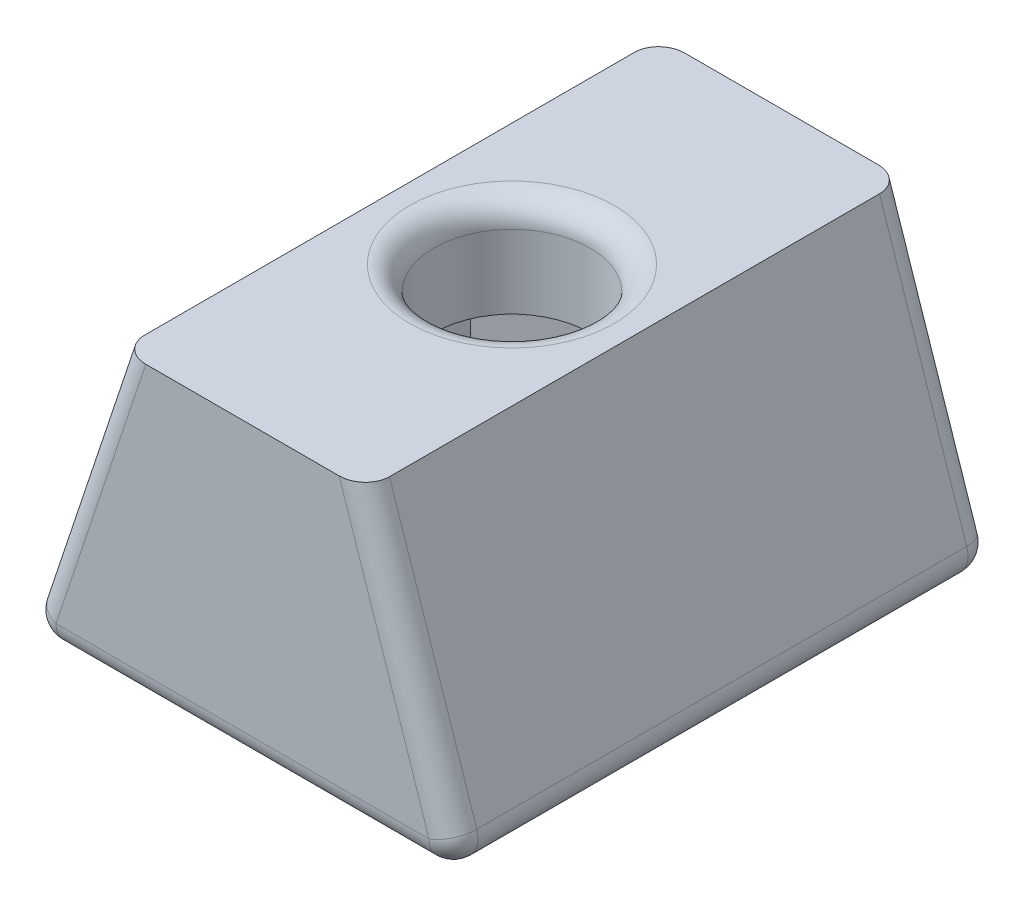
SolidWorks part; units mm, degrees
ref_plane "Front Plane" through (0, 0, 0) normal (0, 0, 1) x (1, 0, 0)
ref_plane "Top Plane" through (0, 0, 0) normal (0, 1, 0) x (1, 0, 0)
ref_plane "Right Plane" through (0, 0, 0) normal (1, 0, 0) x (0, 0, -1)
sketch "Sketch2" plane through (0, 0, 0) normal (0, 0, 1) x (1, 0, 0)
  line L0 (0, 0) -> (18, 0)
  line L1 (18, 0) -> (14.0012, 12)
  line L2 (14.0012, 12) -> (3.9988, 12)
  line L3 (3.9988, 12) -> (0, 0)
  dimension "D1" = 18
  dimension "D2" = 71.57
  dimension "D3" = 71.57
  dimension "D4" = 12
extrude "Boss-Extrude1" add sketch "Sketch2" against normal blind 22
sketch "Sketch3" plane through (0, 0, 0) normal (0, -1, 0) x (1, 0, 0)
  line L0 (0, -22) -> (0, 0) construction
  line L3 (13, -13.3094) -> (13, -8.6906)
  line L4 (13, -8.6906) -> (9, -6.3812)
  line L5 (9, -6.3812) -> (5, -8.6906)
  line L6 (5, -8.6906) -> (5, -13.3094)
  line L7 (5, -13.3094) -> (9, -15.6188)
  line L8 (9, -15.6188) -> (13, -13.3094)
  line L9 (0, 0) -> (18, 0) construction
  line L10 (0, -22) -> (18, -22) construction
  circle A0 centre (9, -11) radius 4 construction
  dimension "D1" = 8
  dimension "D2" = 9
  dimension "D3" = 22
  dimension "D4" = 11
extrude "Cut-Extrude1" cut sketch "Sketch3" against normal blind 8
hole_wizard "1/4 (0.25) Diameter Hole1" positions "Sketch6" profile "Sketch5" hole size "1/4" standard "ANSI Inch" end condition through all
sketch "Sketch6" plane through (0, 12, 0) normal (0, 1, 0) x (1, 0, 0)
  line L0 (14.0012, 22) -> (3.9988, 22) construction
  line L1 (3.9988, 22) -> (3.9988, 0) construction
  point P0 (8.9988, 11)
  dimension "D1" = 11
  dimension "D2" = 5
sketch "Sketch5" plane through (8.9988, 12, -11) normal (1, 0, 0) x (0, 0, 1)
  line L0 (0, 0) -> (0, 12)
  line L1 (0, 12) -> (3.175, 12)
  line L2 (3.175, 12) -> (3.175, 0)
  line L5 (3.175, 0) -> (0, 0)
  line L11 (0, -6.35) -> (0, 107.95) construction
  dimension "Thru Hole Dia." = 6.35
  dimension "Thru Hole Depth" = 12
fillet "Fillet2" radius 1 15 edges at (13, 0, -11) (11, 0, -7.5359) (7, 0, -7.5359) (5, 0, -11) (7, 0, -14.4641) (11, 0, -14.4641) (9, 0, -22) (0, 0, -11) (1.9994, 6, -22) (9, 0, 0) (1.9994, 6, 0) (16.0006, 6, -22) (18, 0, -11) (16.0006, 6, 0) (8.9988, 12, -7.825)
